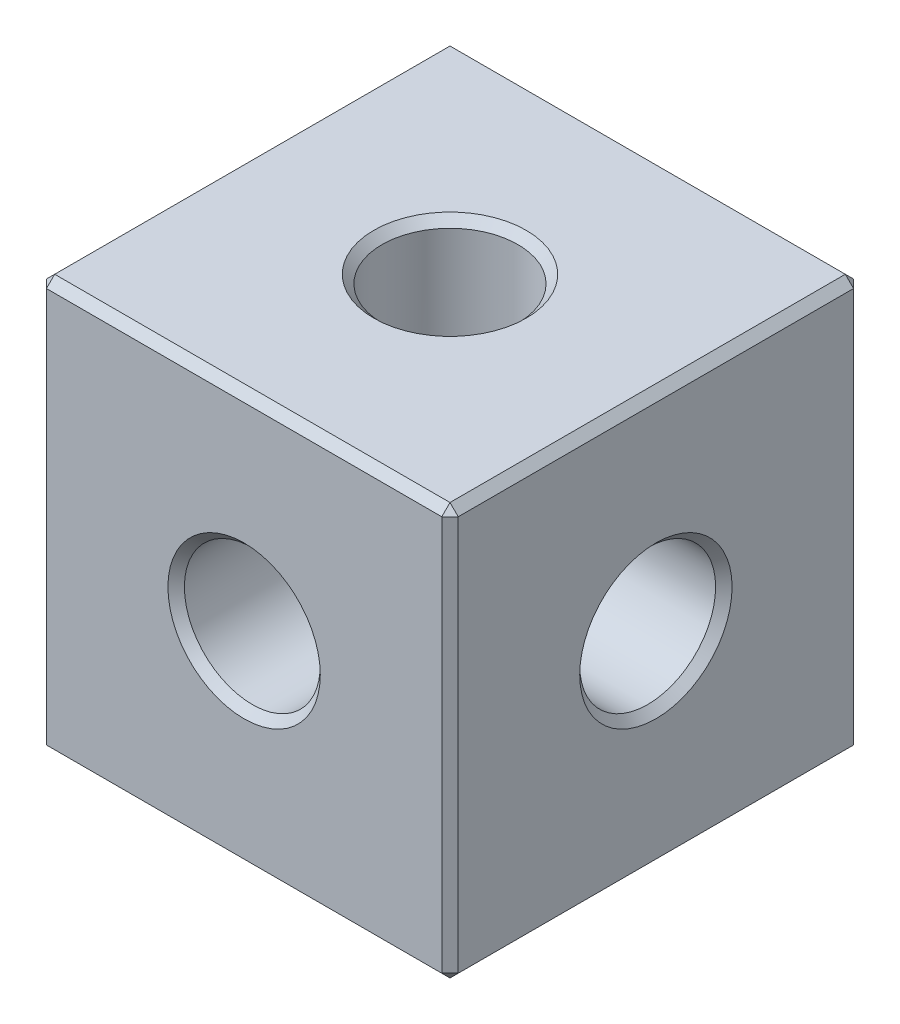
SolidWorks part; units mm, degrees
ref_plane "前视基准面" through (0, 0, 0) normal (0, 0, 1) x (1, 0, 0)
ref_plane "上视基准面" through (0, 0, 0) normal (0, 1, 0) x (1, 0, 0)
ref_plane "右视基准面" through (0, 0, 0) normal (1, 0, 0) x (0, 0, -1)
sketch "草图1" plane through (0, 0, 0) normal (0, 1, 0) x (1, 0, 0)
  line L1 (-5, 5) -> (5, 5)
  line L2 (-5, 5) -> (-5, -5)
  line L3 (-5, -5) -> (5, -5)
  line L4 (5, 5) -> (5, -5)
  line L5 (-5, 5) -> (5, -5) construction
  line L6 (-5, -5) -> (5, 5) construction
  point P0 (0, 0)
  dimension "D1" = 10
extrude "凸台-拉伸1" add sketch "草图1" along normal mid plane 10
hole_wizard "M4 螺纹孔1" positions "草图2" profile "草图3" tap size "M4" standard "GB" end condition through all
sketch "草图2" plane through (0, 0, 5) normal (0, 0, 1) x (1, 0, 0)
  point P0 (0, 0)
sketch "草图3" plane through (0, 0, 5) normal (1, 0, 0) x (0, -1, 0)
  line L0 (0, 0) -> (0, 10)
  line L1 (0, 10) -> (1.65, 10)
  line L2 (1.65, 10) -> (1.65, 0)
  line L5 (1.65, 0) -> (0, 0)
  line L11 (0, -6.35) -> (0, 107.95) construction
  dimension "通孔螺纹孔钻头直径" = 3.3
  dimension "通孔螺纹孔钻头深度" = 10
cosmetic thread "孔螺蚊线1" parameters "D2"=4
hole_wizard "M4 螺纹孔2" positions "草图4" profile "草图5" tap size "M4" standard "GB" end condition through all
sketch "草图4" plane through (0, 5, 0) normal (0, 1, 0) x (1, 0, 0)
  point P0 (0, 0)
sketch "草图5" plane through (0, 5, 0) normal (1, 0, 0) x (0, 0, 1)
  line L0 (0, 0) -> (0, 10)
  line L1 (0, 10) -> (1.65, 10)
  line L2 (1.65, 10) -> (1.65, 0)
  line L5 (1.65, 0) -> (0, 0)
  line L11 (0, -6.35) -> (0, 107.95) construction
  dimension "通孔螺纹孔钻头直径" = 3.3
  dimension "通孔螺纹孔钻头深度" = 10
cosmetic thread "孔螺蚊线2" parameters "D2"=4
hole_wizard "M4 螺纹孔3" positions "草图6" profile "草图7" tap size "M4" standard "GB" end condition through all
sketch "草图6" plane through (5, 0, 0) normal (1, 0, 0) x (0, 0, -1)
  point P0 (0, 0)
sketch "草图7" plane through (5, 0, 0) normal (0, 1, 0) x (0, 0, -1)
  line L0 (0, 0) -> (0, 10)
  line L1 (0, 10) -> (1.65, 10)
  line L2 (1.65, 10) -> (1.65, 0)
  line L5 (1.65, 0) -> (0, 0)
  line L11 (0, -6.35) -> (0, 107.95) construction
  dimension "通孔螺纹孔钻头直径" = 3.3
  dimension "通孔螺纹孔钻头深度" = 10
cosmetic thread "孔螺蚊线3"
chamfer "倒角1" distance 0.2 angle 45 18 edges at (0, -5, 1.65) (-5, 0, -1.65) (1.65, 0, -5) (5, 0, -1.65) (1.65, 0, 5) (-5, -5, 0) (-5, 0, -5) (0, -5, -5) (5, 0, -5) (5, -5, 0) (-5, 0, 5) (0, -5, 5) (5, 0, 5) (0, 5, 5) (-5, 5, 0) (0, 5, -5) (5, 5, 0) (0, 5, 1.65)
